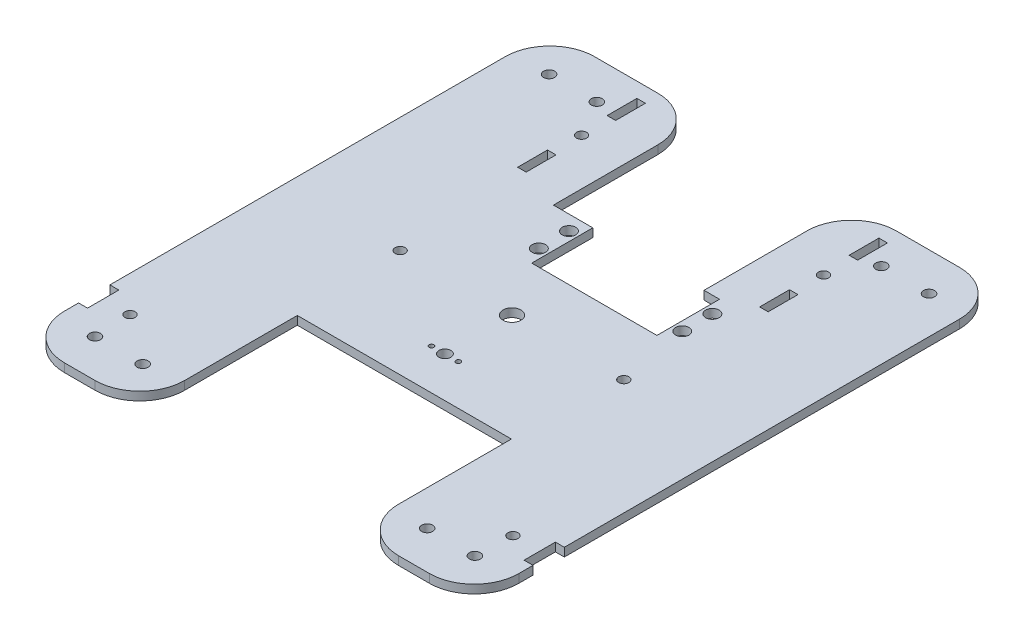
SolidWorks part; units mm, degrees
material "Pine"
ref_plane "Front" through (0, 0, 0) normal (0, 0, 1) x (1, 0, 0)
ref_plane "Top" through (0, 0, 0) normal (0, 1, 0) x (1, 0, 0)
ref_plane "Right" through (0, 0, 0) normal (1, 0, 0) x (0, 0, -1)
sketch "Sketch4" plane through (0, 0, 0) normal (0, 1, 0) x (1, 0, 0)
  line L1 (-76.2, 88.9) -> (76.2, 88.9)
  line L2 (-76.2, 88.9) -> (-76.2, -88.9)
  line L3 (-76.2, -88.9) -> (76.2, -88.9)
  line L4 (76.2, 88.9) -> (76.2, -88.9)
  line L5 (-76.2, 88.9) -> (76.2, -88.9) construction
  line L6 (-76.2, -88.9) -> (76.2, 88.9) construction
  point P0 (0, 0)
  dimension "D1" = 152.4
  dimension "D2" = 177.8
extrude "Boss-Extrude2" add sketch "Sketch4" along normal blind 2.85
sketch "Sketch5" plane through (0, 0, 0) normal (0, -1, 0) x (1, 0, 0)
  line L0 (0, 0) -> (0, -63.9) construction
  line L1 (76.2, -88.9) -> (-76.2, -88.9) construction
  circle A0 centre (0, -63.9) radius 1.5
  dimension "D1" = 3
  dimension "D2" = 25
extrude "Cut-Extrude1" cut sketch "Sketch5" against normal through all
sketch "Sketch6" plane through (0, 2.85, 0) normal (0, 1, 0) x (1, 0, 0)
  circle A0 centre (0, 0) radius 3
  dimension "D1" = 6
extrude "Cut-Extrude2" cut sketch "Sketch6" against normal through all
sketch "Sketch7" plane through (0, 0, 0) normal (0, -1, 0) x (1, 0, 0)
  line L0 (0, 0) -> (37.5, 0) construction
  line L1 (-37.5, 0) -> (0, 0) construction
  circle A0 centre (37.5, 0) radius 1.7
  circle A1 centre (-37.5, 0) radius 1.7
  dimension "D1" = 3.4
  dimension "D2" = 75
extrude "Cut-Extrude3" cut sketch "Sketch7" against normal through all
sketch "Sketch8" plane through (0, 0, 0) normal (0, -1, 0) x (1, 0, 0)
  line L0 (76.2, -88.9) -> (-76.2, -88.9) construction
  line L1 (25, -88.9) -> (-25, -88.9)
  line L2 (25, -88.9) -> (25, -38.9)
  line L3 (25, -38.9) -> (-25, -38.9)
  line L4 (-25, -88.9) -> (-25, -38.9)
  line L5 (0, 0) -> (0, -38.9) construction
  dimension "D1" = 50
  dimension "D2" = 50
extrude "Cut-Extrude4" cut sketch "Sketch8" against normal through all
sketch "Sketch9" plane through (0, 2.85, 0) normal (0, 1, 0) x (1, 0, 0)
  line L0 (-76.2, 88.9) -> (-76.2, -88.9) construction
  line L1 (-76.2, -58.65) -> (-73.2, -58.65)
  line L2 (-76.2, -58.65) -> (-76.2, -69.15)
  line L3 (-76.2, -69.15) -> (-73.2, -69.15)
  line L4 (-73.2, -58.65) -> (-73.2, -69.15)
  line L5 (-73.2, -63.9) -> (-64.2, -63.9) construction
  line L6 (-76.2, -88.9) -> (76.2, -88.9) construction
  circle A0 centre (-64.2, -63.9) radius 1.7
  dimension "D2" = 3.4
  dimension "D1" = 3
  dimension "D3" = 10.5
  dimension "D4" = 25
  dimension "D5" = 12
extrude "Cut-Extrude5" cut sketch "Sketch9" against normal through all
sketch "Sketch10" plane through (0, 0, 0) normal (0, -1, 0) x (1, 0, 0)
  line L0 (-76.2, 88.9) -> (76.2, 88.9) construction
  line L1 (-35.9, 88.9) -> (35.9, 88.9)
  line L2 (-35.9, 88.9) -> (-35.9, 36.1)
  line L3 (-35.9, 36.1) -> (35.9, 36.1)
  line L4 (35.9, 88.9) -> (35.9, 36.1)
  line L5 (0, 0) -> (0, 36.1) construction
  dimension "D1" = 71.8
  dimension "D2" = 52.8
extrude "Cut-Extrude6" cut sketch "Sketch10" against normal through all
sketch "Sketch11" plane through (0, 0, 0) normal (0, -1, 0) x (1, 0, 0)
  line L0 (-11.8, -39.4) -> (30.2, -18.4) construction
  line L1 (30.2, -39.4) -> (-11.8, -39.4)
  line L2 (30.2, -39.4) -> (30.2, -18.4)
  line L3 (30.2, -18.4) -> (-11.8, -18.4)
  line L4 (-11.8, -39.4) -> (-11.8, -18.4)
  line L5 (76.2, 88.9) -> (76.2, -88.9) construction
  line L6 (-14.85, -23.85) -> (33.25, -23.85) construction
  line L7 (-14.85, -23.85) -> (-14.85, -33.95) construction
  line L8 (-14.85, -33.95) -> (33.25, -33.95) construction
  line L9 (33.25, -23.85) -> (33.25, -33.95) construction
  line L10 (-14.85, -23.85) -> (33.25, -33.95) construction
  line L11 (-14.85, -33.95) -> (33.25, -23.85) construction
  line L12 (76.2, -88.9) -> (25, -88.9) construction
  circle A0 centre (-14.85, -23.85) radius 2.25
  circle A1 centre (-14.85, -33.95) radius 2.25
  circle A2 centre (33.25, -33.95) radius 2.25
  circle A3 centre (33.25, -23.85) radius 2.25
  point P4 (9.2, -28.9)
  dimension "D1" = 4.5
  dimension "D2" = 48.1
  dimension "D3" = 10.1
  dimension "D4" = 46
  dimension "D5" = 42
  dimension "D6" = 21
  dimension "D7" = 70.5
extrude "Cut-Extrude7" cut sketch "Sketch11" against normal through all
sketch "Sketch12" plane through (0, 0, 0) normal (0, -1, 0) x (1, 0, 0)
  line L0 (-4.5, 22.5) -> (0, 22.5) construction
  line L1 (0, 22.5) -> (4.5, 22.5) construction
  circle A0 centre (0, 22.5) radius 2
  circle A1 centre (-4.5, 22.5) radius 0.8
  circle A2 centre (4.5, 22.5) radius 0.8
  dimension "D1" = 4
  dimension "D2" = 1.6
  dimension "D3" = 9
extrude "Cut-Extrude8" cut sketch "Sketch12" against normal through all
extrude "Cut-Extrude9" cut sketch "Sketch13" against normal through all
sketch "Sketch13" plane through (0, 4.85, 0) normal (0, 1, 0) x (1, 0, 0)
  circle A0 centre (-63.7, -76.15) radius 1.85
  circle A1 centre (-47.7, -76.15) radius 1.85
mirror "Mirror1" about plane through (0, 0, 0) normal (1, 0, 0) of "Cut-Extrude5"
mirror "Mirror2" about plane through (0, 0, 0) normal (0, 0, 1) of "Cut-Extrude9"
mirror "Mirror3" about plane through (0, 0, 0) normal (1, 0, 0) of "Mirror2", "Cut-Extrude9"
fillet "Fillet1" radius 15 4 edges at (76.2, 1.425, -88.9) (-76.2, 1.425, -88.9) (76.2, 1.425, 88.9) (-76.2, 1.425, 88.9)
fillet "Fillet2" radius 15 4 edges at (35.9, 1.425, 88.9) (25, 1.425, -88.9) (-25, 1.425, -88.9) (-35.9, 1.425, 88.9)
sketch "Sketch14" plane through (0, 0, 0) normal (0, -1, 0) x (1, 0, 0)
  line L0 (61.2, -88.9) -> (40, -88.9) construction
  line L1 (42, -73.9) -> (39.15, -73.9)
  line L2 (42, -73.9) -> (42, -83.9)
  line L3 (42, -83.9) -> (39.15, -83.9)
  line L4 (39.15, -73.9) -> (39.15, -83.9)
  line L5 (42, -43.9) -> (39.15, -43.9)
  line L6 (42, -43.9) -> (42, -53.9)
  line L7 (42, -53.9) -> (39.15, -53.9)
  line L8 (39.15, -43.9) -> (39.15, -53.9)
  line L9 (25, -73.9) -> (25, -39.4) construction
  line L10 (40.575, -53.9) -> (40.575, -63.9) construction
  line L11 (40.575, -63.9) -> (40.575, -73.9) construction
  circle A0 centre (40.575, -63.9) radius 1.7
  dimension "D6" = 3.4
  dimension "D1" = 10
  dimension "D2" = 5
  dimension "D3" = 20
  dimension "D4" = 14.15
  dimension "D5" = 2.85
extrude "Cut-Extrude10" cut sketch "Sketch14" against normal through all
mirror "Mirror4" about plane through (0, 0, 0) normal (1, 0, 0) of "Cut-Extrude10"
